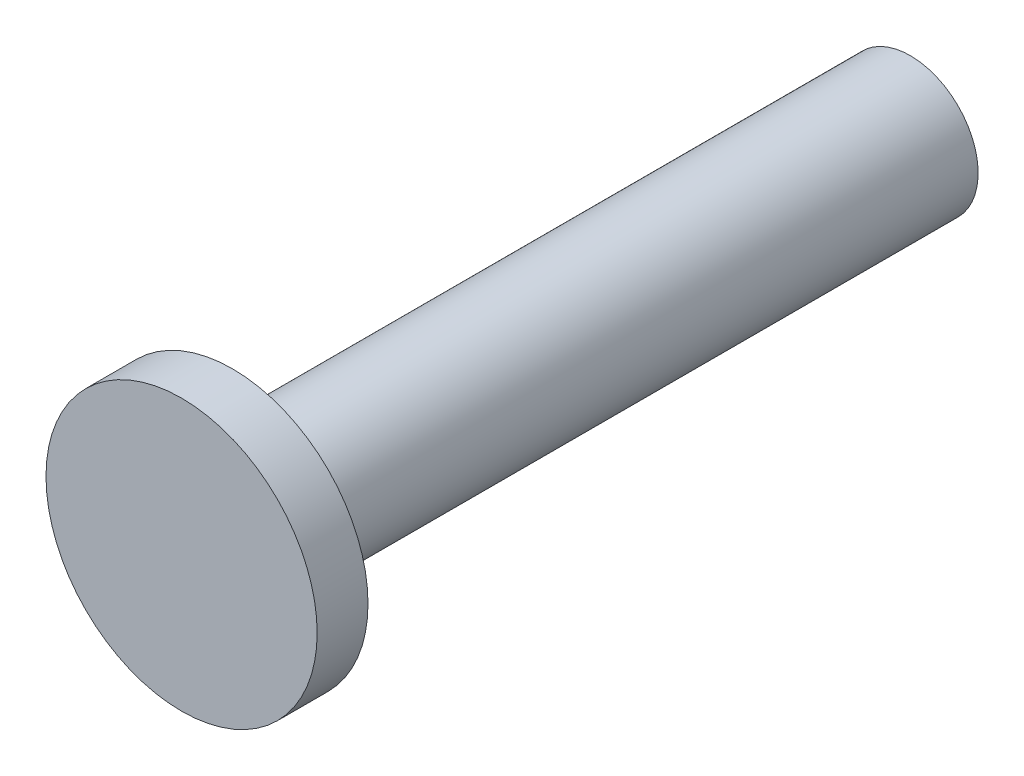
SolidWorks part; units mm, degrees
ref_plane "Plan de face" through (0, 0, 0) normal (0, 0, 1) x (1, 0, 0)
ref_plane "Plan de dessus" through (0, 0, 0) normal (0, 1, 0) x (1, 0, 0)
ref_plane "Plan de droite" through (0, 0, 0) normal (1, 0, 0) x (0, 0, -1)
sketch "Esquisse1" plane through (0, 0, 0) normal (0, 0, 1) x (1, 0, 0)
  circle A0 centre (0, 0) radius 4
  dimension "D1" = 8
extrude "Boss.-Extru.1" add sketch "Esquisse1" along normal blind 1.5
sketch "Esquisse2" plane through (0, 0, 0) normal (0, 0, -1) x (-1, 0, 0)
  circle A0 centre (0, 0) radius 2
  dimension "D1" = 4
extrude "Boss.-Extru.2" add sketch "Esquisse2" along normal blind 20
